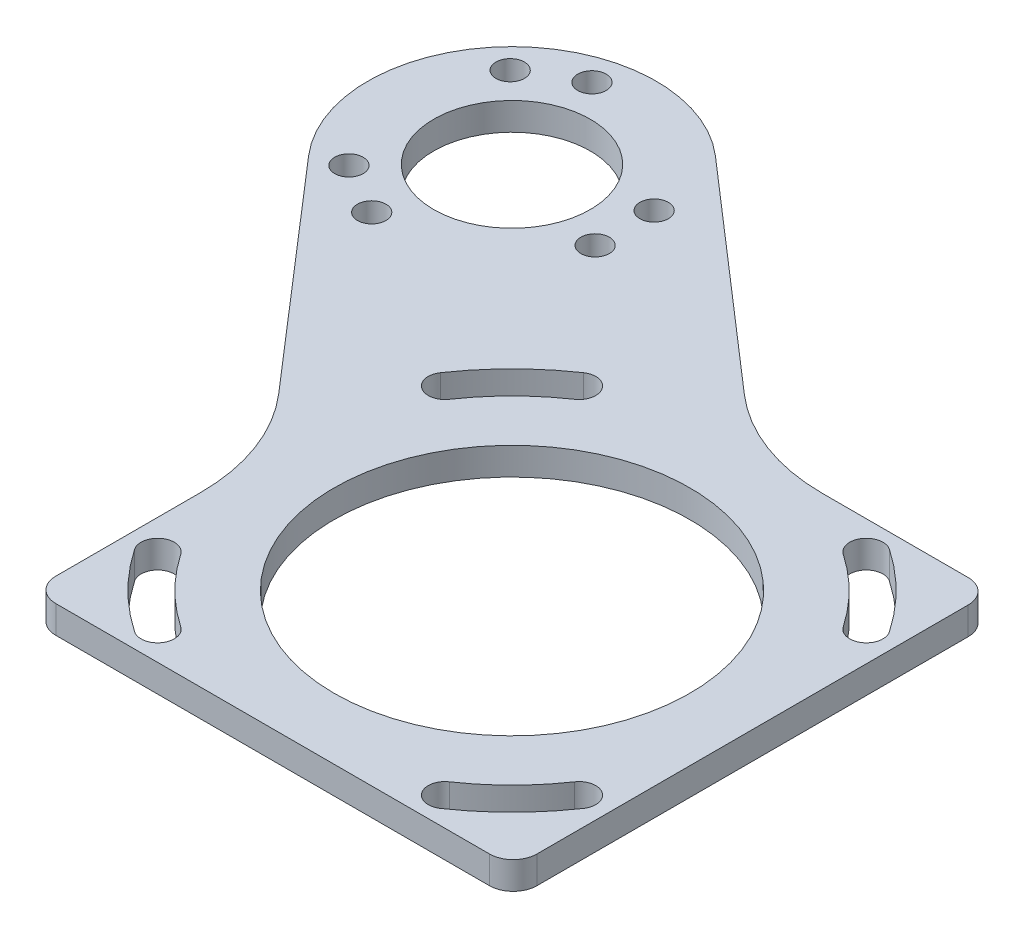
SolidWorks part; units mm, degrees
ref_plane "Front Plane" through (0, 0, 0) normal (0, 0, 1) x (1, 0, 0)
ref_plane "Top Plane" through (0, 0, 0) normal (0, 1, 0) x (1, 0, 0)
ref_plane "Right Plane" through (0, 0, 0) normal (1, 0, 0) x (0, 0, -1)
sketch "Sketch1" plane through (0, 0, 0) normal (0, 1, 0) x (1, 0, 0)
  line L0 (0, 48.26) -> (48.26, 0) construction
  line L1 (24.13, 24.13) -> (56.3247, 24.13) construction
  line L2 (-8.0647, 56.1631) -> (56.3247, 56.1631) construction
  line L3 (-8.0647, 56.1631) -> (-8.0647, -7.9031) construction
  line L4 (-8.0647, -7.9031) -> (56.3247, -7.9031) construction
  line L5 (56.3247, 56.1631) -> (56.3247, -7.9031) construction
  line L6 (-8.0647, 56.1631) -> (56.3247, -7.9031) construction
  line L7 (-8.0647, -7.9031) -> (56.3247, 56.1631) construction
  line L8 (24.13, 24.13) -> (24.13, 56.1631) construction
  line L9 (-25.2614, 73.5214) -> (24.13, 24.13) construction
  line L10 (24.13, 24.13) -> (-46.1461, 24.13) construction
  line L11 (-8.0647, 24.13) -> (24.13, 56.1631) construction
  line L12 (24.13, 56.1631) -> (-12.6027, 88.087) construction
  line L13 (-8.0647, 24.13) -> (-39.8587, 60.8993) construction
  line L14 (-8.0647, -4.7281) -> (-8.0647, 14.6713)
  line L15 (-12.6027, 88.087) -> (16.9633, 62.3916)
  line L16 (33.625, 56.1631) -> (53.1497, 56.1631)
  line L17 (56.3247, 52.9881) -> (56.3247, -4.7281)
  line L18 (53.1497, -7.9031) -> (-4.8897, -7.9031)
  line L19 (-14.2514, 31.2848) -> (-39.8587, 60.8993)
  circle A0 centre (0, 0) radius 2.2225 construction
  circle A1 centre (48.26, 0) radius 2.2225 construction
  circle A2 centre (48.26, 48.26) radius 2.2225 construction
  circle A3 centre (0, 48.26) radius 2.2225 construction
  circle A4 centre (24.13, 24.13) radius 23.8125
  circle A5 centre (24.13, 24.13) radius 34.125 construction
  arc A6 (52.3287, 4.9116) -> (43.3484, -4.0687) centre (24.13, 24.13) cw construction
  arc A7 (44.6001, -5.9052) -> (54.1652, 3.6599) centre (24.13, 24.13) ccw
  arc A8 (42.0968, -2.2322) -> (50.4922, 6.1632) centre (24.13, 24.13) ccw
  arc A9 (42.0968, -2.2322) -> (44.6001, -5.9052) centre (43.3484, -4.0687) ccw
  arc A10 (54.1652, 3.6599) -> (50.4922, 6.1632) centre (52.3287, 4.9116) ccw
  arc A11 (52.3287, 43.3484) -> (43.3484, 52.3287) centre (24.13, 24.13) ccw construction
  arc A12 (44.6001, 54.1652) -> (54.1652, 44.6001) centre (24.13, 24.13) cw
  arc A13 (42.0968, 50.4922) -> (50.4922, 42.0968) centre (24.13, 24.13) cw
  arc A14 (42.0968, 50.4922) -> (44.6001, 54.1652) centre (43.3484, 52.3287) cw
  arc A15 (54.1652, 44.6001) -> (50.4922, 42.0968) centre (52.3287, 43.3484) cw
  arc A16 (-4.0687, 4.9116) -> (4.9116, -4.0687) centre (24.13, 24.13) ccw construction
  arc A17 (3.6599, -5.9052) -> (-5.9052, 3.6599) centre (24.13, 24.13) cw
  arc A18 (6.1632, -2.2322) -> (-2.2322, 6.1632) centre (24.13, 24.13) cw
  arc A19 (6.1632, -2.2322) -> (3.6599, -5.9052) centre (4.9116, -4.0687) cw
  arc A20 (-5.9052, 3.6599) -> (-2.2322, 6.1632) centre (-4.0687, 4.9116) cw
  arc A21 (-4.0687, 43.3484) -> (4.9116, 52.3287) centre (24.13, 24.13) cw construction
  arc A22 (3.6599, 54.1652) -> (-5.9052, 44.6001) centre (24.13, 24.13) ccw
  arc A23 (6.1632, 50.4922) -> (-2.2322, 42.0968) centre (24.13, 24.13) ccw
  arc A24 (6.1632, 50.4922) -> (3.6599, 54.1652) centre (4.9116, 52.3287) ccw
  arc A25 (-5.9052, 44.6001) -> (-2.2322, 42.0968) centre (-4.0687, 43.3484) ccw
  circle A26 centre (-25.2614, 73.5214) radius 10.4775
  arc A27 (-12.6027, 88.087) -> (-39.8587, 60.8993) centre (-25.2614, 73.5214) ccw construction
  arc A28 (-12.6027, 88.087) -> (-39.8587, 60.8993) centre (-25.2614, 73.5214) ccw
  arc A29 (-8.0647, 14.6713) -> (-14.2514, 31.2848) centre (-33.4647, 14.6713) ccw
  arc A30 (16.9633, 62.3916) -> (33.625, 56.1631) centre (33.625, 81.5631) ccw
  arc A31 (53.1497, 56.1631) -> (56.3247, 52.9881) centre (53.1497, 52.9881) cw
  arc A32 (56.3247, -4.7281) -> (53.1497, -7.9031) centre (53.1497, -4.7281) cw
  arc A33 (-8.0647, -4.7281) -> (-4.8897, -7.9031) centre (-4.8897, -4.7281) ccw
  circle A34 centre (-25.2614, 73.5214) radius 15.4305 construction
  circle A35 centre (-36.294, 84.3094) radius 1.905
  circle A36 centre (-29.4219, 88.3804) radius 1.905
  circle A37 centre (-21.435, 88.47) radius 1.905 [skipped]
  circle A38 centre (-14.4734, 84.554) radius 1.905 [skipped]
  circle A39 centre (-10.4024, 77.6819) radius 1.905
  circle A40 centre (-10.3129, 69.695) radius 1.905
  circle A41 centre (-14.2288, 62.7334) radius 1.905 [skipped]
  circle A42 centre (-21.1009, 58.6624) radius 1.905 [skipped]
  circle A43 centre (-29.0878, 58.5729) radius 1.905
  circle A44 centre (-36.0494, 62.4888) radius 1.905
  circle A45 centre (-40.1204, 69.3609) radius 1.905 [skipped]
  circle A46 centre (-40.21, 77.3478) radius 1.905 [skipped]
  point P19 (48.26, 0)
  point P28 (48.26, 48.26)
  point P35 (0, 0)
  point P42 (0, 48.26)
  dimension "D1" = 4.445
  dimension "D4" = 47.625
  dimension "D7" = 4.445
  dimension "D9" = 20.955
  dimension "D10" = 38.5953
  dimension "D15" = 25.4
  dimension "D16" = 3.175
  dimension "D17" = 30.861
  dimension "D18" = 3.81
  dimension "D19" = 12
  dimension "D5" = 48.26
  dimension "D8" = 12.7
  dimension "D11" = 45
  dimension "D12" = 69.85
  dimension "D13" = 48.609
  dimension "D14" = 48.6665
  dimension "D20" = 7.9874
  dimension "D21" = 48.26
  dimension "D2" = 2
  dimension "D3" = 2
extrude "Boss-Extrude1" add sketch "Sketch1" along normal blind 3.683
